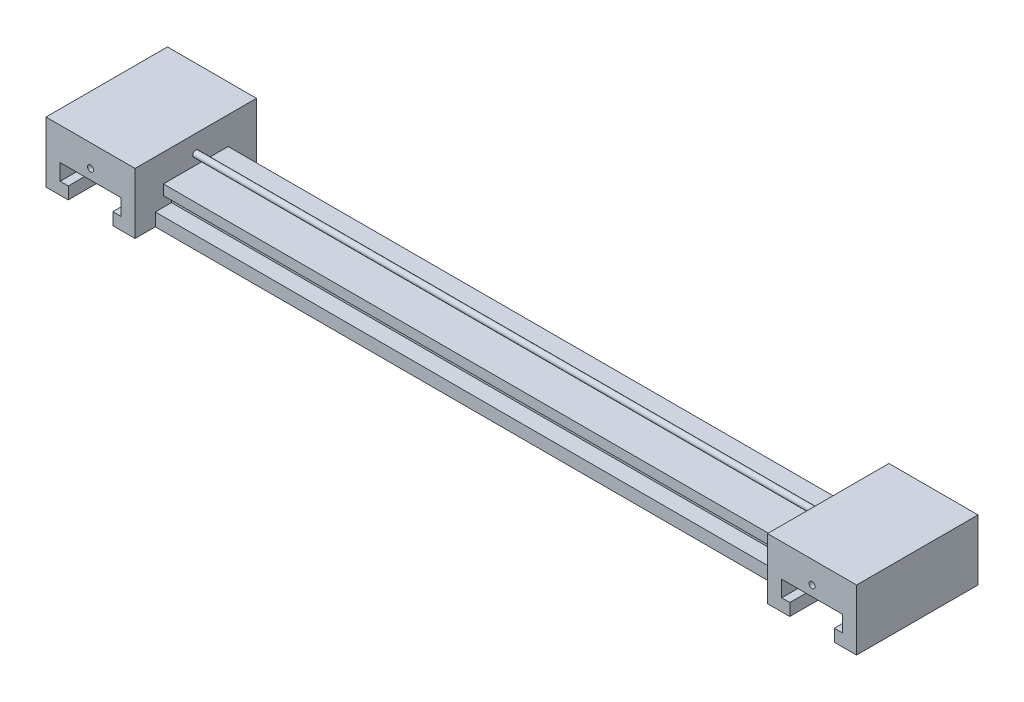
SolidWorks part; units mm, degrees
ref_plane "前视基准面" through (0, 0, 0) normal (0, 0, 1) x (1, 0, 0)
ref_plane "上视基准面" through (0, 0, 0) normal (0, 1, 0) x (1, 0, 0)
ref_plane "右视基准面" through (0, 0, 0) normal (1, 0, 0) x (0, 0, -1)
sketch "草图1" plane through (0, 0, 0) normal (0, 0, 1) x (1, 0, 0)
  line L3 (-231.1746, 10.7321) -> (-220.1746, 10.7321)
  line L4 (-194.1746, 24.7321) -> (-224.1746, 24.7321)
  line L6 (-224.1746, 24.7321) -> (-224.1746, 16.7321)
  line L7 (-224.1746, 16.7321) -> (-220.1746, 16.7321)
  line L8 (-220.1746, 16.7321) -> (-220.1746, 10.7321)
  line L9 (-198.1746, 16.7321) -> (-198.1746, 10.7321)
  line L10 (-194.1746, 16.7321) -> (-198.1746, 16.7321)
  line L11 (-194.1746, 24.7321) -> (-194.1746, 16.7321)
  line L12 (-198.1746, 10.7321) -> (-187.1746, 10.7321)
  line L24 (-187.1746, 10.7321) -> (-187.1746, 40.7321)
  line L25 (-187.1746, 40.7321) -> (-231.1746, 40.7321)
  line L26 (-231.1746, 40.7321) -> (-231.1746, 10.7321)
  line L27 (-209.1746, 24.7321) -> (-209.1746, 29.7321) construction
  line L40 (136.3254, 16.7321) -> (136.3254, 10.7321)
  line L41 (162.3254, 16.7321) -> (158.3254, 16.7321)
  line L42 (158.3254, 10.7321) -> (169.3254, 10.7321)
  line L43 (147.3254, 24.7321) -> (147.3254, 29.7321) construction
  line L44 (162.3254, 24.7321) -> (162.3254, 16.7321)
  line L45 (125.3254, 40.7321) -> (125.3254, 10.7321)
  line L46 (132.3254, 16.7321) -> (136.3254, 16.7321)
  line L47 (158.3254, 16.7321) -> (158.3254, 10.7321)
  line L48 (132.3254, 24.7321) -> (132.3254, 16.7321)
  line L49 (169.3254, 40.7321) -> (125.3254, 40.7321)
  line L50 (169.3254, 10.7321) -> (169.3254, 40.7321)
  line L51 (125.3254, 10.7321) -> (136.3254, 10.7321)
  line L52 (162.3254, 24.7321) -> (132.3254, 24.7321)
  circle A0 centre (-209.1746, 29.7321) radius 1.5
  circle A2 centre (147.3254, 29.7321) radius 1.5
  dimension "D3" = 6
  dimension "D1" = 11
  dimension "D2" = 30
  dimension "D4" = 4
  dimension "D5" = 4
  dimension "D6" = 44
  dimension "D7" = 8
  dimension "D8" = 11
  dimension "D9" = 6
  dimension "D10" = 5
  dimension "D11" = 30
  dimension "D12" = 8
extrude "凸台-拉伸1" add sketch "草图1" along normal blind 60
sketch "草图2" plane through (-187.1746, 0, 0) normal (1, 0, 0) x (0, 0, -1)
  line L0 (-10, 10.7321) -> (-50, 10.7321)
  line L2 (-50, 10.7321) -> (-50, 17.1025)
  line L3 (-50, 17.1025) -> (-42, 17.1025)
  line L4 (-42, 17.1025) -> (-42, 22.1025)
  line L5 (-42, 22.1025) -> (-46, 22.1025)
  line L6 (-46, 22.1025) -> (-46, 27.1025)
  line L7 (-46, 27.1025) -> (-14, 27.1025)
  line L8 (-30, 24) -> (-30, 7.6296) construction
  line L9 (-14, 22.1025) -> (-14, 27.1025)
  line L10 (-18, 22.1025) -> (-14, 22.1025)
  line L11 (-18, 17.1025) -> (-18, 22.1025)
  line L12 (-10, 17.1025) -> (-18, 17.1025)
  line L13 (-10, 10.7321) -> (-10, 17.1025)
  line L14 (-60, 10.7321) -> (0, 10.7321) construction
  circle A0 centre (-30, 32.1025) radius 1.5
extrude "凸台-拉伸2" add sketch "草图2" along normal blind 312.5
